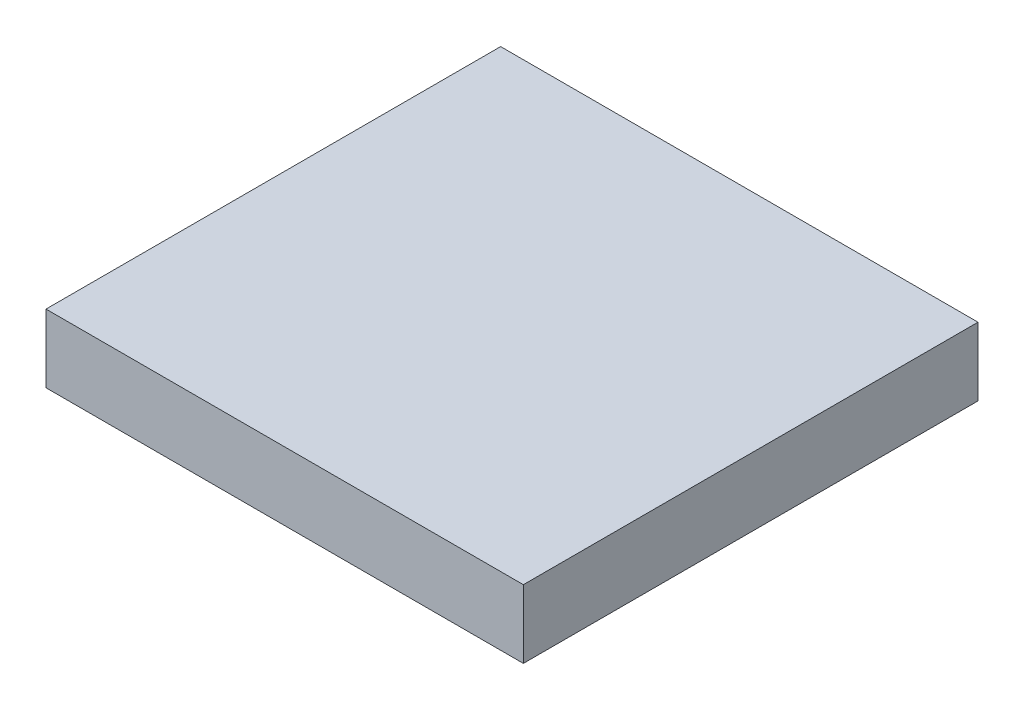
SolidWorks part; units mm, degrees
ref_plane "Front Plane" through (0, 0, 0) normal (0, 0, 1) x (1, 0, 0)
ref_plane "Top Plane" through (0, 0, 0) normal (0, 1, 0) x (1, 0, 0)
ref_plane "Right Plane" through (0, 0, 0) normal (1, 0, 0) x (0, 0, -1)
sketch "Sketch1" plane through (0, 0, 0) normal (0, 1, 0) x (1, 0, 0)
  line L1 (-21, 20) -> (21, 20)
  line L2 (-21, 20) -> (-21, -20)
  line L3 (-21, -20) -> (21, -20)
  line L4 (21, 20) -> (21, -20)
  line L5 (-21, 20) -> (21, -20) construction
  line L6 (-21, -20) -> (21, 20) construction
  point P0 (0, 0)
  dimension "D1" = 42
  dimension "D2" = 40
extrude "Boss-Extrude1" add sketch "Sketch1" along normal blind 6
